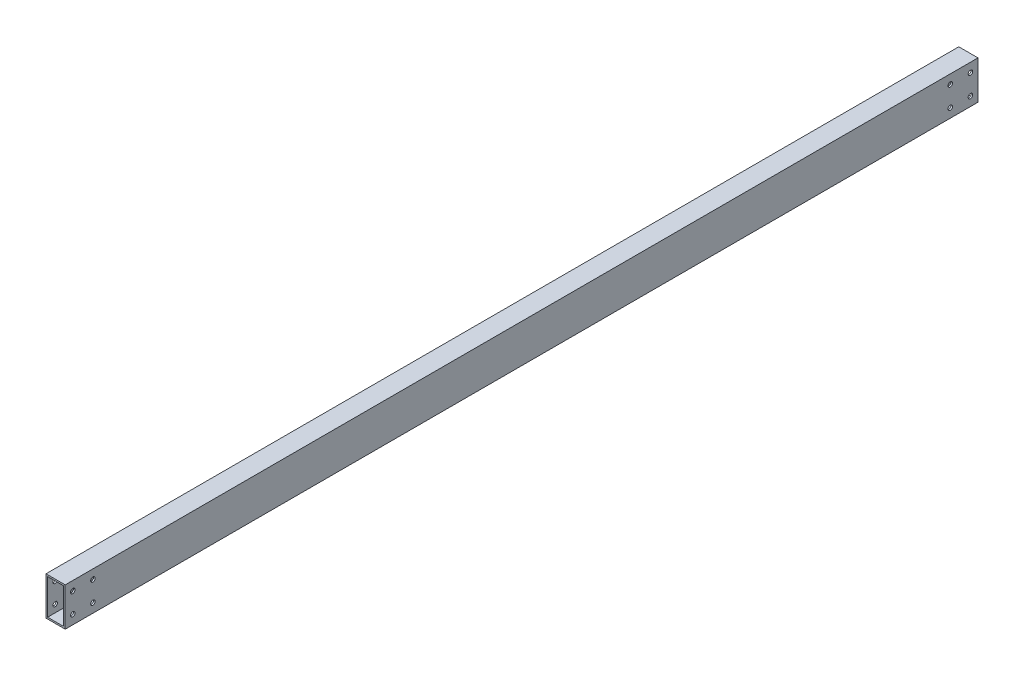
SolidWorks part; units mm, degrees
material "6063-T6"
ref_plane "Front Plane" through (0, 0, 0) normal (0, 0, 1) x (1, 0, 0)
ref_plane "Top Plane" through (0, 0, 0) normal (0, 1, 0) x (1, 0, 0)
ref_plane "Right Plane" through (0, 0, 0) normal (1, 0, 0) x (0, 0, -1)
sketch "Sketch1" plane through (0, 0, 0) normal (0, 0, 1) x (1, 0, 0)
  line L1 (-19.05, 38.1) -> (19.05, 38.1)
  line L2 (-19.05, 38.1) -> (-19.05, -38.1)
  line L3 (-19.05, -38.1) -> (19.05, -38.1)
  line L4 (19.05, 38.1) -> (19.05, -38.1)
  line L5 (-19.05, 38.1) -> (19.05, -38.1) construction
  line L6 (-19.05, -38.1) -> (19.05, 38.1) construction
  point P0 (0, 0)
  dimension "D1" = 38.1
  dimension "D2" = 76.2
extrude "Extrude-Thin1" add sketch "Sketch1" along normal mid plane 1810 thin
hole_wizard "M8 Clearance Hole2" positions "Sketch2" profile "Sketch3" hole size "M8" standard "ANSI Metric"
sketch "Sketch2" plane through (19.05, 0, 0) normal (1, 0, 0) x (0, 0, -1)
  line L1 (-890, 20) -> (-850, 20)
  line L2 (-890, 20) -> (-890, -20)
  line L3 (-890, -20) -> (-850, -20)
  line L4 (-850, 20) -> (-850, -20)
  line L5 (20.955, 0) -> (-20.955, 0) construction
  line L6 (-905, -38.1) -> (-905, 38.1) construction
  point P1 (-890, 20)
  point P2 (-850, -20)
  point P89 (-890, -20)
  point P90 (-850, 20)
  point P92 (-850, 0)
  dimension "D1" = 40
  dimension "D2" = 15
sketch "Sketch3" plane through (19.05, 20, 890) normal (0, 1, 0) x (0, 0, -1)
  line L0 (0, 0) -> (0, 3.175)
  line L1 (0, 3.175) -> (4.5, 3.175)
  line L2 (4.5, 3.175) -> (4.5, 0)
  line L5 (4.5, 0) -> (0, 0)
  line L11 (0, -6.35) -> (0, 107.95) construction
  dimension "Thru Hole Dia." = 9
  dimension "Thru Hole Depth" = 3.175
hole_wizard "M8 Clearance Hole1" positions "Sketch4" profile "Sketch5" hole size "M8" standard "ANSI Metric" end condition up to next
sketch "Sketch4" plane through (-15.875, 0, 0) normal (1, 0, 0) x (0, 0, -1)
  point P0 (-890, 20)
  point P3 (-850, 20)
  point P6 (-850, -20)
  point P9 (-890, -20)
sketch "Sketch5" plane through (-15.875, 20, 890) normal (0, 1, 0) x (0, 0, -1)
  line L0 (0, 0) -> (0, 3.175)
  line L1 (0, 3.175) -> (4.5, 3.175)
  line L2 (4.5, 3.175) -> (4.5, 0)
  line L5 (4.5, 0) -> (0, 0)
  line L11 (0, -6.35) -> (0, 107.95) construction
  dimension "Thru Hole Dia." = 9
  dimension "Thru Hole Depth" = 3.175
mirror "Mirror1" about plane through (0, 0, 0) normal (0, 0, 1) of "M8 Clearance Hole1", "M8 Clearance Hole2"
